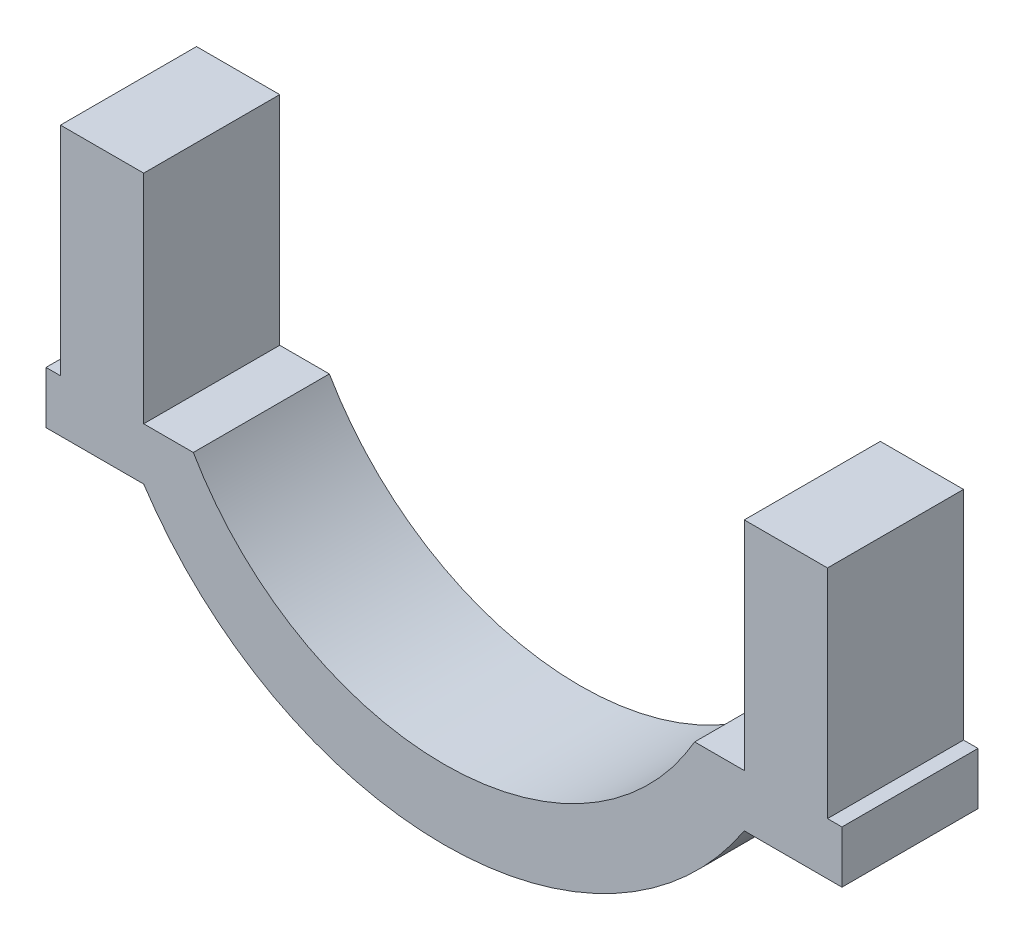
SolidWorks part; units mm, degrees
ref_plane "Front Plane" through (0, 0, 0) normal (0, 0, 1) x (1, 0, 0)
ref_plane "Top Plane" through (0, 0, 0) normal (0, 1, 0) x (1, 0, 0)
ref_plane "Right Plane" through (0, 0, 0) normal (1, 0, 0) x (0, 0, -1)
sketch "Sketch1" plane through (0, 0, 0) normal (0, 0, 1) x (1, 0, 0)
  line L0 (41.5, -20) -> (34.641, -20)
  line L1 (53, 10) -> (41.5, 10)
  line L2 (53, 10) -> (53, -20)
  line L3 (55, -20) -> (55, -27.2123)
  line L4 (41.5, 10) -> (41.5, -20)
  line L5 (-41.5, 10) -> (-53, 10)
  line L6 (-41.5, 10) -> (-41.5, -20)
  line L7 (55, -27.2123) -> (41.5, -27.2123)
  line L8 (-53, 10) -> (-53, -20)
  line L9 (-41.5, -20) -> (-34.641, -20)
  line L10 (53, -20) -> (55, -20)
  line L11 (-53, -20) -> (-55, -20)
  line L12 (0, 0) -> (0, -25.011) construction
  line L13 (-55, -20) -> (-55, -27.2123)
  line L14 (-55, -27.2123) -> (-41.5, -27.2123)
  arc A1 (34.641, -20) -> (-34.641, -20) centre (0, 0) cw
  arc A2 (41.5, -27.2123) -> (-41.5, -27.2123) centre (0, 0) cw
  point P4 (0, 0)
  point P5 (0, 0)
  point P10 (0, 0)
  point P11 (0, 0)
  point P14 (0, 0)
  dimension "D1" = 40
  dimension "D3" = 13.5
  dimension "D10" = 49.6262
  dimension "D2" = 6.859
  dimension "D4" = 6.859
  dimension "D5" = 2
  dimension "D6" = 30
  dimension "D7" = 7.2123
  dimension "D8" = 30
  dimension "D9" = 11.5
  dimension "D11" = 34.641
  dimension "D12" = 13.5
  dimension "D13" = 7.2123
  dimension "D14" = 11.5
  dimension "D15" = 30
  dimension "D16" = 30
  dimension "D17" = 2
  dimension "D18" = 108
extrude "Boss-Extrude1" add sketch "Sketch1" against normal blind 18.8
